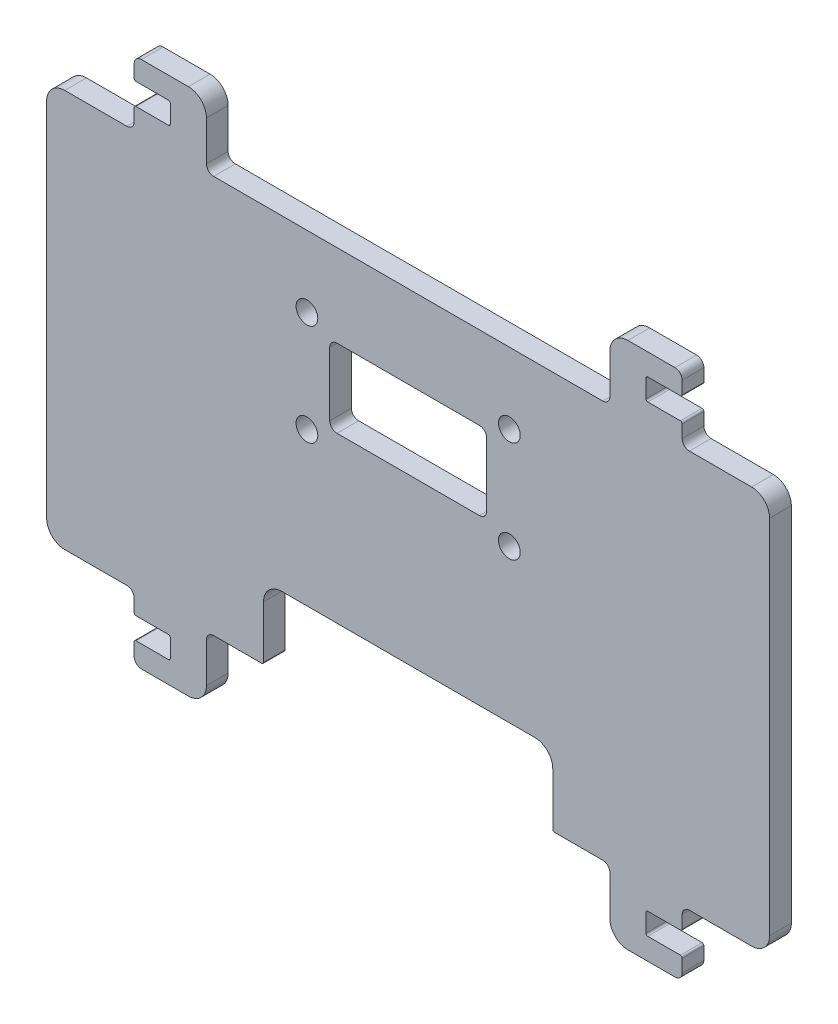
SolidWorks part; units mm, degrees
ref_plane "Alzado" through (0, 0, 0) normal (0, 0, 1) x (1, 0, 0)
ref_plane "Planta" through (0, 0, 0) normal (0, 1, 0) x (1, 0, 0)
ref_plane "Vista lateral" through (0, 0, 0) normal (1, 0, 0) x (0, 0, -1)
sketch "Croquis1" plane through (0, 0, 0) normal (0, 0, 1) x (1, 0, 0)
  line L0 (0, 16.0534) -> (0, 17.6634) construction
  line L2 (-50, 25) -> (-50, -25)
  line L4 (50, 25) -> (50, -25)
  line L5 (-50, 27.5) -> (50, -27.5) construction
  line L6 (-50, -27.5) -> (50, 27.5) construction
  line L7 (-10.85, 16.0534) -> (10.85, 16.0534)
  line L8 (-10.85, 16.0534) -> (-10.85, 5.2534)
  line L9 (-10.85, 5.2534) -> (10.85, 5.2534)
  line L10 (10.85, 16.0534) -> (10.85, 5.2534)
  line L11 (-10.85, 16.0534) -> (10.85, 5.2534) construction
  line L12 (-10.85, 5.2534) -> (10.85, 16.0534) construction
  line L13 (-14, 17.6634) -> (14, 17.6634) construction
  line L14 (0, 12.2207) -> (0, 8.6829) construction
  line L15 (-2.0239, 10.6534) -> (1.9478, 10.6534) construction
  line L23 (0, 2.3088) -> (0, -3.2784) construction
  line L31 (-47.5, -27.5) -> (-37.9, -27.5)
  line L33 (37.9, -27.5) -> (47.5, -27.5)
  line L34 (-37.9, 27.5) -> (-37.9, 30.5)
  line L35 (-37.9, 30.5) -> (-32.9, 30.5)
  line L36 (-32.9, 30.5) -> (-32.9, 33.5)
  line L37 (-32.9, 33.5) -> (-37.9, 33.5)
  line L38 (-37.9, 33.5) -> (-37.9, 36.5)
  line L39 (-37.9, 36.5) -> (-30.4, 36.5)
  line L48 (-47.5, 27.5) -> (-37.9, 27.5)
  line L50 (37.9, 27.5) -> (47.5, 27.5)
  line L51 (37.9, -27.5) -> (-37.9, -27.5) construction
  line L52 (-27.9, 34) -> (-27.9, 27.5)
  line L53 (37.9, 27.5) -> (37.9, 30.5)
  line L54 (37.9, 30.5) -> (32.9, 30.5)
  line L55 (32.9, 30.5) -> (32.9, 33.5)
  line L56 (32.9, 33.5) -> (37.9, 33.5)
  line L57 (37.9, 33.5) -> (37.9, 36.5)
  line L58 (37.9, 36.5) -> (30.4, 36.5)
  line L59 (27.9, 34) -> (27.9, 27.5)
  line L60 (-27.9, 27.5) -> (27.9, 27.5)
  line L61 (-2.1702, 0) -> (2.1702, 0) construction
  line L62 (37.9, -27.5) -> (37.9, -30.5)
  line L63 (27.9, -34) -> (27.9, -27.5)
  line L64 (-27.9, -27.5) -> (27.9, -27.5)
  line L65 (-27.9, -34) -> (-27.9, -27.5)
  line L66 (-37.9, -30.5) -> (-32.9, -30.5)
  line L67 (-37.9, -27.5) -> (-37.9, -30.5)
  line L68 (37.9, -36.5) -> (30.4, -36.5)
  line L69 (37.9, -33.5) -> (37.9, -36.5)
  line L70 (32.9, -33.5) -> (37.9, -33.5)
  line L71 (32.9, -30.5) -> (32.9, -33.5)
  line L72 (37.9, -30.5) -> (32.9, -30.5)
  line L73 (-37.9, -36.5) -> (-30.4, -36.5)
  line L74 (-37.9, -33.5) -> (-37.9, -36.5)
  line L75 (-32.9, -33.5) -> (-37.9, -33.5)
  line L76 (-32.9, -30.5) -> (-32.9, -33.5)
  circle A0 centre (-14, 17.6634) radius 1.5
  circle A1 centre (14, 17.6634) radius 1.5
  circle A2 centre (14, 3.6434) radius 1.5
  circle A3 centre (-14, 3.6434) radius 1.5
  arc A4 (-50, -25) -> (-47.5, -27.5) centre (-47.5, -25) ccw
  arc A5 (47.5, -27.5) -> (50, -25) centre (47.5, -25) ccw
  arc A8 (47.5, 27.5) -> (50, 25) centre (47.5, 25) cw
  arc A10 (-30.4, 36.5) -> (-27.9, 34) centre (-30.4, 34) cw
  arc A11 (-47.5, 27.5) -> (-50, 25) centre (-47.5, 25) ccw
  arc A12 (30.4, 36.5) -> (27.9, 34) centre (30.4, 34) ccw
  arc A13 (30.4, -36.5) -> (27.9, -34) centre (30.4, -34) cw
  arc A14 (-30.4, -36.5) -> (-27.9, -34) centre (-30.4, -34) ccw
  point P0 (0, 0)
  point P6 (0, 10.6534)
  point P16 (0, 17.6634)
  point P26 (-37.9, -27.5)
  point P32 (0, 0)
  point P81 (-27.9, 36.5)
  point P85 (-27.9, -36.5)
  dimension "D7" = 3
  dimension "D21" = 2.5
  dimension "D1" = 100
  dimension "D2" = 55
  dimension "D3" = 21.7
  dimension "D4" = 10.8
  dimension "D5" = 1.61
  dimension "D6" = 28
  dimension "D15" = 10
  dimension "D16" = 3
  dimension "D17" = 3
  dimension "D18" = 3
  dimension "D19" = 5
  dimension "D20" = 5
extrude "Saliente-Extruir1" add sketch "Croquis1" along normal blind 3
sketch "Croquis2" plane through (0, 0, 0) normal (0, 0, 1) x (1, 0, 0)
  line L1 (-17.5, -17.5) -> (17.5, -17.5)
  line L2 (-20, -20) -> (-20, -37.5)
  line L3 (-20, -37.5) -> (20, -37.5)
  line L4 (20, -20) -> (20, -37.5)
  line L5 (-20, -17.5) -> (20, -37.5) construction
  line L6 (-20, -37.5) -> (20, -17.5) construction
  arc A0 (17.5, -17.5) -> (20, -20) centre (17.5, -20) cw
  arc A1 (-17.5, -17.5) -> (-20, -20) centre (-17.5, -20) ccw
  point P0 (0, -27.5)
  dimension "D3" = 2.5
  dimension "D1" = 40
  dimension "D2" = 20
extrude "Cortar-Extruir2" cut sketch "Croquis2" against normal mid plane 6 contours L3 L4 A0 L1 A1 L2
fillet "Redondeo1" radius 1 16 edges at (-10.85, 5.2534, 1.5) (10.85, 5.2534, 1.5) (10.85, 16.0534, 1.5) (-10.85, 16.0534, 1.5) (-37.9, 27.5, 1.5) (-37.9, 36.5, 1.5) (-37.9, -36.5, 1.5) (-37.9, -27.5, 1.5) (37.9, -36.5, 1.5) (37.9, -27.5, 1.5) (37.9, 27.5, 1.5) (37.9, 36.5, 1.5) (27.9, -27.5, 1.5) (-27.9, -27.5, 1.5) (-27.9, 27.5, 1.5) (27.9, 27.5, 1.5)
fillet "Redondeo2" radius 0.25 18 edges at (-32.9, -33.5, 1.5) (-37.9, -33.5, 1.5) (-32.9, -30.5, 1.5) (-37.9, -30.5, 1.5) (20, -27.5, 1.5) (-20, -27.5, 1.5) (32.9, -33.5, 1.5) (32.9, -30.5, 1.5) (37.9, -33.5, 1.5) (37.9, -30.5, 1.5) (37.9, 33.5, 1.5) (32.9, 33.5, 1.5) (37.9, 30.5, 1.5) (32.9, 30.5, 1.5) (-37.9, 30.5, 1.5) (-37.9, 33.5, 1.5) (-32.9, 33.5, 1.5) (-32.9, 30.5, 1.5)
